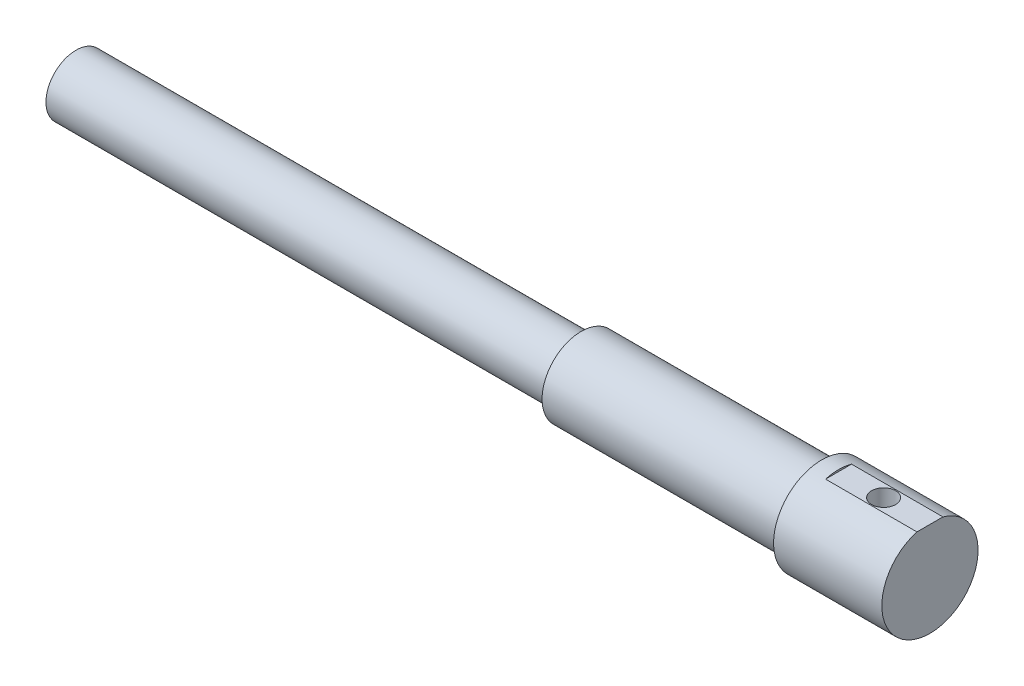
SolidWorks part; units mm, degrees
material "AISI 316 Barra de acero inoxidable recocido (SS)"
ref_plane "Alzado" through (0, 0, 0) normal (0, 0, 1) x (1, 0, 0)
ref_plane "Planta" through (0, 0, 0) normal (0, 1, 0) x (1, 0, 0)
ref_plane "Vista lateral" through (0, 0, 0) normal (1, 0, 0) x (0, 0, -1)
sketch "Croquis2" plane through (0, 0, 0) normal (1, 0, 0) x (0, 0, -1)
  circle A0 centre (0, 0) radius 12.5
  dimension "D1" = 25
extrude "Saliente-Extruir1" add sketch "Croquis2" along normal blind 210
sketch "Croquis4" plane through (210, 0, 0) normal (1, 0, 0) x (0, 0, -1)
  circle A0 centre (0, 0) radius 16.25
  dimension "D1" = 32.5
extrude "Saliente-Extruir2" add sketch "Croquis4" along normal blind 100
sketch "Croquis5" plane through (310, 0, 0) normal (1, 0, 0) x (0, 0, -1)
  circle A0 centre (0, 0) radius 20
extrude "Saliente-Extruir3" add sketch "Croquis5" along normal blind 45
sketch "Croquis6" plane through (355, 0, 0) normal (1, 0, 0) x (0, 0, -1)
  line L1 (-5.3998, 20.7428) -> (5.3998, 20.7428)
  line L2 (-5.3998, 20.7428) -> (-5.3998, 19.2572)
  line L3 (-5.3998, 19.2572) -> (5.3998, 19.2572)
  line L4 (5.3998, 20.7428) -> (5.3998, 19.2572)
  line L5 (-5.3998, 20.7428) -> (5.3998, 19.2572) construction
  line L6 (-5.3998, 19.2572) -> (5.3998, 20.7428) construction
  circle A0 centre (0, 0) radius 20 construction
  point P0 (0, 20)
extrude "Cortar-Extruir1" cut sketch "Croquis6" against normal blind 38
sketch "Croquis8" plane through (0, 19.2572, 0) normal (0, 1, 0) x (1, 0, 0)
  circle A0 centre (335.7302, 0) radius 5
  dimension "D1" = 10
extrude "Cortar-Extruir2" cut sketch "Croquis8" against normal up to next
